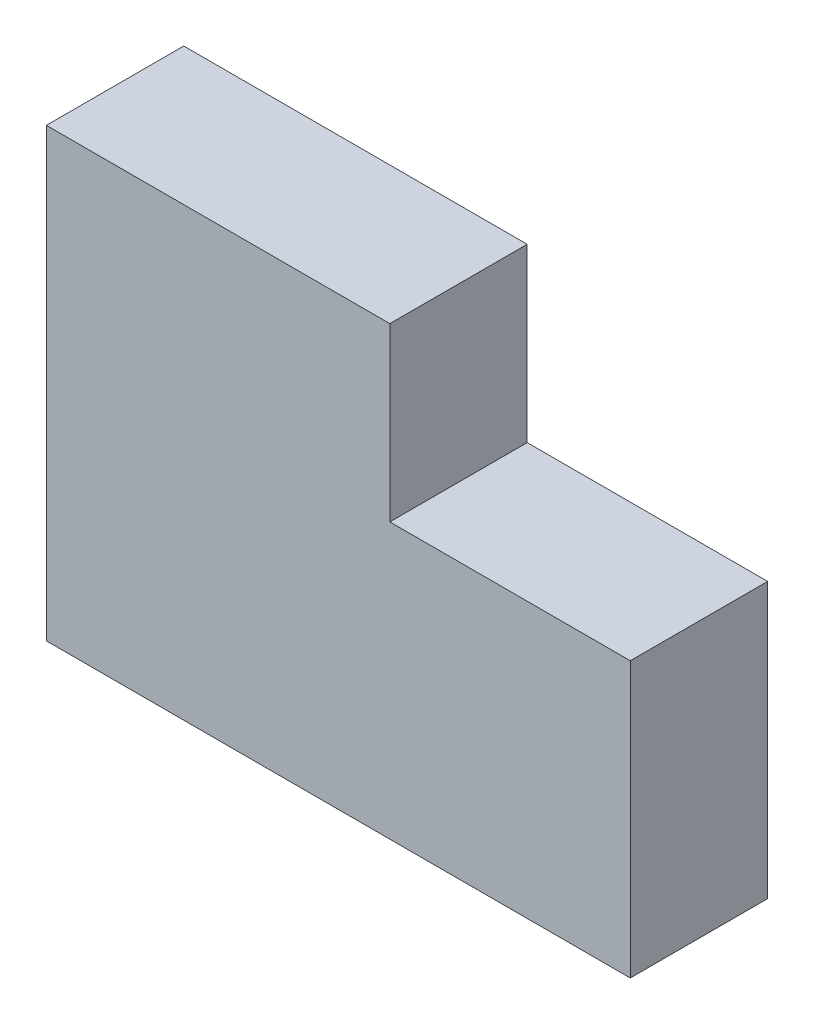
SolidWorks part; units mm, degrees
ref_plane "Front Plane" through (0, 0, 0) normal (0, 0, 1) x (1, 0, 0)
ref_plane "Top Plane" through (0, 0, 0) normal (0, 1, 0) x (1, 0, 0)
ref_plane "Right Plane" through (0, 0, 0) normal (1, 0, 0) x (0, 0, -1)
sketch "Sketch1" plane through (0, 0, 0) normal (0, 0, 1) x (1, 0, 0)
  line L0 (0, 0) -> (85, 0)
  line L1 (0, 0) -> (0, 65)
  line L2 (0, 65) -> (50, 65)
  line L3 (50, 65) -> (50, 40)
  line L4 (85, 0) -> (85, 40)
  line L5 (50, 40) -> (85, 40)
  dimension "D1" = 65
  dimension "D2" = 50
  dimension "D3" = 40
  dimension "D4" = 85
extrude "Boss-Extrude1" add sketch "Sketch1" along normal blind 20
